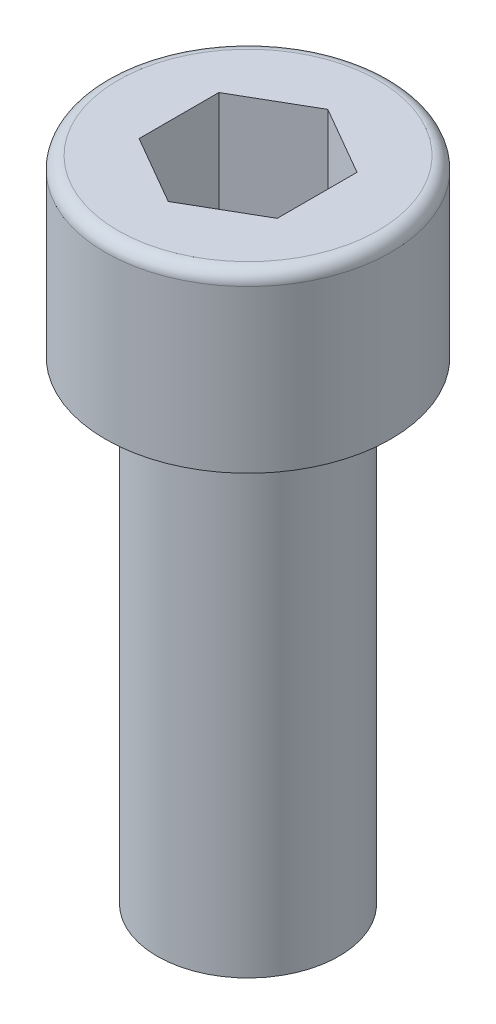
SolidWorks part; units mm, degrees
ref_plane "Front Plane" through (0, 0, 0) normal (0, 0, 1) x (1, 0, 0)
ref_plane "Top Plane" through (0, 0, 0) normal (0, 1, 0) x (1, 0, 0)
ref_plane "Right Plane" through (0, 0, 0) normal (1, 0, 0) x (0, 0, -1)
sketch "Sketch1" plane through (0, 0, 0) normal (0, 1, 0) x (1, 0, 0)
  circle A0 centre (0, 0) radius 1.8288
  dimension "D1" = 3.6576
extrude "Boss-Extrude1" add sketch "Sketch1" against normal blind 9.525
sketch "Sketch2" plane through (0, 0, 0) normal (0, 1, 0) x (1, 0, 0)
  circle A0 centre (0, 0) radius 2.8702
  dimension "D1" = 5.7404
extrude "Boss-Extrude2" add sketch "Sketch2" along normal blind 3.5052
fillet "Fillet1" radius 0.254 1 edges at (0, 3.5052, 2.8702)
sketch "Sketch3" plane through (0, 3.5052, 0) normal (0, 1, 0) x (1, 0, 0)
  line L1 (0, 1.604) -> (-1.3891, 0.802)
  line L2 (-1.3891, 0.802) -> (-1.3891, -0.802)
  line L3 (-1.3891, -0.802) -> (0, -1.604)
  line L4 (0, -1.604) -> (1.3891, -0.802)
  line L5 (1.3891, -0.802) -> (1.3891, 0.802)
  line L6 (1.3891, 0.802) -> (0, 1.604)
  circle A0 centre (0, 0) radius 1.3891 construction
  dimension "D1" = 2.7781
extrude "Cut-Extrude1" cut sketch "Sketch3" against normal blind 2.54
